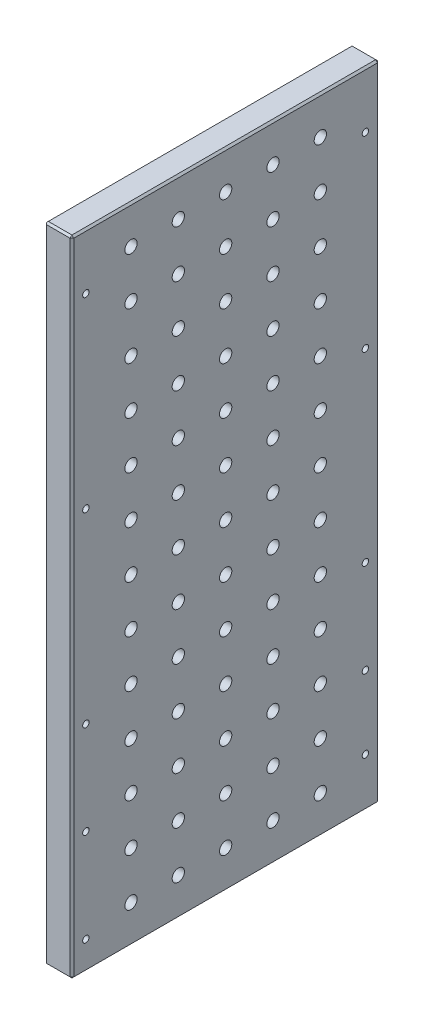
SolidWorks part; units mm, degrees
ref_plane "Front Plane" through (0, 0, 0) normal (0, 0, 1) x (1, 0, 0)
ref_plane "Top Plane" through (0, 0, 0) normal (0, 1, 0) x (1, 0, 0)
ref_plane "Right Plane" through (0, 0, 0) normal (1, 0, 0) x (0, 0, -1)
ref_plane "Plane1" through (137.16, 0, 0) normal (1, 0, 0) x (0, 0, -1)
sketch "Sketch1" plane through (137.16, 0, 0) normal (1, 0, 0) x (0, 0, -1)
  line L0 (82.5015, 242.88) -> (82.5015, 588.18)
  line L1 (82.5015, 588.18) -> (-82.4985, 588.18)
  line L2 (-82.4985, 588.18) -> (-82.4985, 242.88)
  line L3 (-82.4985, 242.88) -> (82.5015, 242.88)
  circle A0 centre (-75, 258.18) radius 2.08
  circle A1 centre (75, 269.1126) radius 2.08
  circle A2 centre (75, 308.18) radius 2.08
  circle A3 centre (75, 358.2689) radius 2.08
  circle A4 centre (-75, 308.18) radius 2.08
  circle A5 centre (-75, 358.18) radius 2.08
  circle A6 centre (75, 457.7157) radius 2.08
  circle A7 centre (-75, 458.18) radius 2.08
  circle A8 centre (75, 558.18) radius 2.08
  circle A9 centre (-75, 558.18) radius 2.08
  circle A10 centre (-25.3985, 517.13) radius 3.3
  circle A11 centre (50.8015, 517.13) radius 3.3
  circle A12 centre (25.4015, 517.13) radius 3.3
  circle A13 centre (50.8015, 567.93) radius 3.3
  circle A14 centre (50.8015, 542.53) radius 3.3
  circle A15 centre (0.0015, 567.93) radius 3.3
  circle A16 centre (0.0015, 517.13) radius 3.3
  circle A17 centre (25.4015, 542.53) radius 3.3
  circle A18 centre (25.4015, 567.93) radius 3.3
  circle A19 centre (-50.7985, 567.93) radius 3.3
  circle A20 centre (-25.3985, 567.93) radius 3.3
  circle A21 centre (0.0015, 542.53) radius 3.3
  circle A22 centre (-50.7985, 542.53) radius 3.3
  circle A23 centre (-50.7985, 491.73) radius 3.3
  circle A24 centre (-25.3985, 491.73) radius 3.3
  circle A25 centre (-25.3985, 542.53) radius 3.3
  circle A26 centre (-50.7985, 517.13) radius 3.3
  circle A27 centre (50.8015, 415.53) radius 3.3
  circle A28 centre (50.8015, 440.93) radius 3.3
  circle A29 centre (0.0015, 415.53) radius 3.3
  circle A30 centre (25.4015, 415.53) radius 3.3
  circle A31 centre (-25.3985, 440.93) radius 3.3
  circle A32 centre (-50.7985, 440.93) radius 3.3
  circle A33 centre (25.4015, 440.93) radius 3.3
  circle A34 centre (0.0015, 440.93) radius 3.3
  circle A35 centre (0.0015, 466.33) radius 3.3
  circle A36 centre (25.4015, 466.33) radius 3.3
  circle A37 centre (-50.7985, 466.33) radius 3.3
  circle A38 centre (-25.3985, 466.33) radius 3.3
  circle A39 centre (25.4015, 491.73) radius 3.3
  circle A40 centre (0.0015, 491.73) radius 3.3
  circle A41 centre (50.8015, 466.33) radius 3.3
  circle A42 centre (50.8015, 491.73) radius 3.3
  circle A43 centre (25.4015, 390.13) radius 3.3
  circle A44 centre (0.0015, 390.13) radius 3.3
  circle A45 centre (50.8015, 364.73) radius 3.3
  circle A46 centre (50.8015, 390.13) radius 3.3
  circle A47 centre (-50.7985, 415.53) radius 3.3
  circle A48 centre (-25.3985, 415.53) radius 3.3
  circle A49 centre (-25.3985, 390.13) radius 3.3
  circle A50 centre (-50.7985, 390.13) radius 3.3
  circle A51 centre (-25.3985, 339.33) radius 3.3
  circle A52 centre (-50.7985, 339.33) radius 3.3
  circle A53 centre (25.4015, 339.33) radius 3.3
  circle A54 centre (0.0015, 339.33) radius 3.3
  circle A55 centre (0.0015, 364.73) radius 3.3
  circle A56 centre (25.4015, 364.73) radius 3.3
  circle A57 centre (-50.7985, 364.73) radius 3.3
  circle A58 centre (-25.3985, 364.73) radius 3.3
  circle A59 centre (-50.7985, 313.93) radius 3.3
  circle A60 centre (-25.3985, 313.93) radius 3.3
  circle A61 centre (-25.3985, 288.53) radius 3.3
  circle A62 centre (-50.7985, 288.53) radius 3.3
  circle A63 centre (50.8015, 313.93) radius 3.3
  circle A64 centre (50.8015, 339.33) radius 3.3
  circle A65 centre (0.0015, 313.93) radius 3.3
  circle A66 centre (25.4015, 313.93) radius 3.3
  circle A67 centre (50.8015, 288.53) radius 3.3
  circle A68 centre (50.8015, 263.13) radius 3.3
  circle A69 centre (0.0015, 288.53) radius 3.3
  circle A70 centre (25.4015, 288.53) radius 3.3
  circle A71 centre (-25.3985, 263.13) radius 3.3
  circle A72 centre (-50.7985, 263.13) radius 3.3
  circle A73 centre (25.4015, 263.13) radius 3.3
  circle A74 centre (0.0015, 263.13) radius 3.3
extrude "Boss-Extrude1" add sketch "Sketch1" against normal blind 14.66
sketch "Sketch2" plane through (122.5, 0, 0) normal (-1, 0, 0) x (0, 0, 1)
  circle A0 centre (-50.8015, 263.13) radius 5.5
  circle A1 centre (-25.4015, 263.13) radius 5.5
  circle A2 centre (-0.0015, 263.13) radius 5.5
  circle A3 centre (25.3985, 263.13) radius 5.5
  circle A4 centre (50.7985, 263.13) radius 5.5
  circle A5 centre (-25.4015, 288.53) radius 5.5
  circle A6 centre (-0.0015, 288.53) radius 5.5
  circle A7 centre (25.3985, 288.53) radius 5.5
  circle A8 centre (50.7985, 288.53) radius 5.5
  circle A9 centre (-25.4015, 313.93) radius 5.5
  circle A10 centre (-0.0015, 313.93) radius 5.5
  circle A11 centre (25.3985, 313.93) radius 5.5
  circle A12 centre (50.7985, 313.93) radius 5.5
  circle A13 centre (-25.4015, 339.33) radius 5.5
  circle A14 centre (-0.0015, 339.33) radius 5.5
  circle A15 centre (25.3985, 339.33) radius 5.5
  circle A16 centre (50.7985, 339.33) radius 5.5
  circle A17 centre (-25.4015, 364.73) radius 5.5
  circle A18 centre (-0.0015, 364.73) radius 5.5
  circle A19 centre (25.3985, 364.73) radius 5.5
  circle A20 centre (50.7985, 364.73) radius 5.5
  circle A21 centre (-25.4015, 390.13) radius 5.5
  circle A22 centre (-0.0015, 390.13) radius 5.5
  circle A23 centre (25.3985, 390.13) radius 5.5
  circle A24 centre (50.7985, 390.13) radius 5.5
  circle A25 centre (-25.4015, 415.53) radius 5.5
  circle A26 centre (-0.0015, 415.53) radius 5.5
  circle A27 centre (25.3985, 415.53) radius 5.5
  circle A28 centre (50.7985, 415.53) radius 5.5
  circle A29 centre (-25.4015, 440.93) radius 5.5
  circle A30 centre (-0.0015, 440.93) radius 5.5
  circle A31 centre (25.3985, 440.93) radius 5.5
  circle A32 centre (50.7985, 440.93) radius 5.5
  circle A33 centre (-25.4015, 466.33) radius 5.5
  circle A34 centre (-0.0015, 466.33) radius 5.5
  circle A35 centre (25.3985, 466.33) radius 5.5
  circle A36 centre (50.7985, 466.33) radius 5.5
  circle A37 centre (-25.4015, 491.73) radius 5.5
  circle A38 centre (-0.0015, 491.73) radius 5.5
  circle A39 centre (25.3985, 491.73) radius 5.5
  circle A40 centre (50.7985, 491.73) radius 5.5
  circle A41 centre (-25.4015, 517.13) radius 5.5
  circle A42 centre (-0.0015, 517.13) radius 5.5
  circle A43 centre (25.3985, 517.13) radius 5.5
  circle A44 centre (50.7985, 517.13) radius 5.5
  circle A45 centre (-25.4015, 542.53) radius 5.5
  circle A46 centre (-0.0015, 542.53) radius 5.5
  circle A47 centre (25.3985, 542.53) radius 5.5
  circle A48 centre (50.7985, 542.53) radius 5.5
  circle A49 centre (-25.4015, 567.93) radius 5.5
  circle A50 centre (-0.0015, 567.93) radius 5.5
  circle A51 centre (25.3985, 567.93) radius 5.5
  circle A52 centre (50.7985, 567.93) radius 5.5
  circle A53 centre (-50.8015, 288.53) radius 5.5
  circle A54 centre (-50.8015, 313.93) radius 5.5
  circle A55 centre (-50.8015, 339.33) radius 5.5
  circle A56 centre (-50.8015, 364.73) radius 5.5
  circle A57 centre (-50.8015, 390.13) radius 5.5
  circle A58 centre (-50.8015, 415.53) radius 5.5
  circle A59 centre (-50.8015, 440.93) radius 5.5
  circle A60 centre (-50.8015, 466.33) radius 5.5
  circle A61 centre (-50.8015, 491.73) radius 5.5
  circle A62 centre (-50.8015, 517.13) radius 5.5
  circle A63 centre (-50.8015, 542.53) radius 5.5
  circle A64 centre (-50.8015, 567.93) radius 5.5
extrude "Cut-Extrude1" cut sketch "Sketch2" against normal blind 8
chamfer "Chamfer1" distance 1 angle 45 79 edges at (122.5, 415.53, -82.5015) (122.5, 588.18, -0.0015) (122.5, 415.53, 82.4985) (122.5, 242.88, -0.0015) (122.5, 258.18, 77.08) (122.5, 269.1126, -72.92) (122.5, 308.18, -72.92) (122.5, 358.2689, -72.92) (122.5, 308.18, 77.08) (122.5, 358.18, 77.08) (122.5, 457.7157, -72.92) (122.5, 458.18, 77.08) (122.5, 558.18, -72.92) (122.5, 558.18, 77.08) (122.5, 263.13, -45.3015) (122.5, 466.33, -19.9015) (122.5, 466.33, 5.4985) (122.5, 466.33, 30.8985) (122.5, 466.33, 56.2985) (122.5, 491.73, -19.9015) (122.5, 491.73, 5.4985) (122.5, 491.73, 30.8985) (122.5, 491.73, 56.2985) (122.5, 517.13, -19.9015) (122.5, 517.13, 5.4985) (122.5, 517.13, 30.8985) (122.5, 517.13, 56.2985) (122.5, 542.53, -19.9015) (122.5, 542.53, 5.4985) (122.5, 542.53, 30.8985) (122.5, 542.53, 56.2985) (122.5, 567.93, -45.3015) (122.5, 542.53, -45.3015) (122.5, 517.13, -45.3015) (122.5, 491.73, -45.3015) (122.5, 466.33, -45.3015) (122.5, 440.93, -45.3015) (122.5, 415.53, -45.3015) (122.5, 390.13, -45.3015) (122.5, 364.73, -45.3015) (122.5, 339.33, -45.3015) (122.5, 313.93, -45.3015) (122.5, 288.53, -45.3015) (122.5, 567.93, 56.2985) (122.5, 567.93, 30.8985) (122.5, 567.93, 5.4985) (122.5, 567.93, -19.9015) (122.5, 440.93, 56.2985) (122.5, 440.93, 30.8985) (122.5, 440.93, 5.4985) (122.5, 440.93, -19.9015) (122.5, 415.53, 56.2985) (122.5, 415.53, 30.8985) (122.5, 415.53, 5.4985) (122.5, 415.53, -19.9015) (122.5, 390.13, 56.2985) (122.5, 390.13, 30.8985) (122.5, 390.13, 5.4985) (122.5, 390.13, -19.9015) (122.5, 364.73, 56.2985) (122.5, 364.73, 30.8985) (122.5, 364.73, 5.4985) (122.5, 364.73, -19.9015) (122.5, 339.33, 56.2985) (122.5, 339.33, 30.8985) (122.5, 339.33, 5.4985) (122.5, 339.33, -19.9015) (122.5, 313.93, 56.2985) (122.5, 313.93, 30.8985) (122.5, 313.93, 5.4985) (122.5, 313.93, -19.9015) (122.5, 288.53, 56.2985) (122.5, 288.53, 30.8985) (122.5, 288.53, 5.4985) (122.5, 288.53, -19.9015) (122.5, 263.13, 56.2985) (122.5, 263.13, 30.8985) (122.5, 263.13, 5.4985) (122.5, 263.13, -19.9015)
chamfer "Chamfer2" distance 1 angle 45 8 edges at (130.33, 588.18, -82.5015) (137.16, 588.18, -0.0015) (130.33, 588.18, 82.4985) (137.16, 415.53, 82.4985) (130.33, 242.88, 82.4985) (137.16, 242.88, -0.0015) (137.16, 415.53, -82.5015) (130.33, 242.88, -82.5015)
sketch "Sketch3" plane through (122.5, 0, 0) normal (-1, 0, 0) x (0, 0, 1)
  circle A0 centre (-75, 558.18) radius 3.08
  circle A1 centre (-75, 558.18) radius 1.725
  circle A2 centre (75, 558.18) radius 3.08
  circle A3 centre (75, 558.18) radius 1.725
  circle A4 centre (75, 458.18) radius 3.08
  circle A5 centre (75, 458.18) radius 1.725
  circle A6 centre (-75, 457.7157) radius 3.08
  circle A7 centre (-75, 457.7157) radius 1.725
  circle A8 centre (-75, 358.2689) radius 3.08
  circle A9 centre (-75, 358.2689) radius 1.725
  circle A10 centre (75, 358.18) radius 3.08
  circle A11 centre (75, 358.18) radius 1.725
  circle A12 centre (75, 308.18) radius 3.08
  circle A13 centre (75, 308.18) radius 1.725
  circle A14 centre (75, 258.18) radius 3.08
  circle A15 centre (75, 258.18) radius 1.725
  circle A16 centre (-75, 269.1126) radius 3.08
  circle A17 centre (-75, 269.1126) radius 1.725
  circle A18 centre (-75, 308.18) radius 3.08
  circle A19 centre (-75, 308.18) radius 1.725
extrude "Boss-Extrude2" add sketch "Sketch3" against normal up to surface (14.66 mm away) up to face at (137.16, 415.53, -0.0015)
